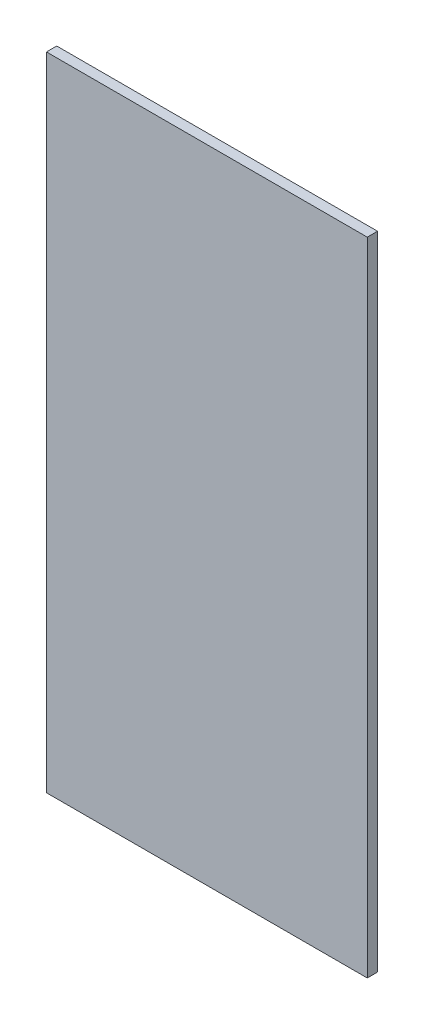
SolidWorks part; units mm, degrees
ref_plane "Front Plane" through (0, 0, 0) normal (0, 0, 1) x (1, 0, 0)
ref_plane "Top Plane" through (0, 0, 0) normal (0, 1, 0) x (1, 0, 0)
ref_plane "Right Plane" through (0, 0, 0) normal (1, 0, 0) x (0, 0, -1)
sketch "Sketch1" plane through (0, 0, 0) normal (0, 0, 1) x (1, 0, 0)
  line L1 (0, 0) -> (50, 0)
  line L2 (0, 0) -> (0, -100)
  line L3 (0, -100) -> (50, -100)
  line L4 (50, 0) -> (50, -100)
  dimension "D1" = 50
  dimension "D2" = 100
extrude "Boss-Extrude1" add sketch "Sketch1" along normal blind 1.6
